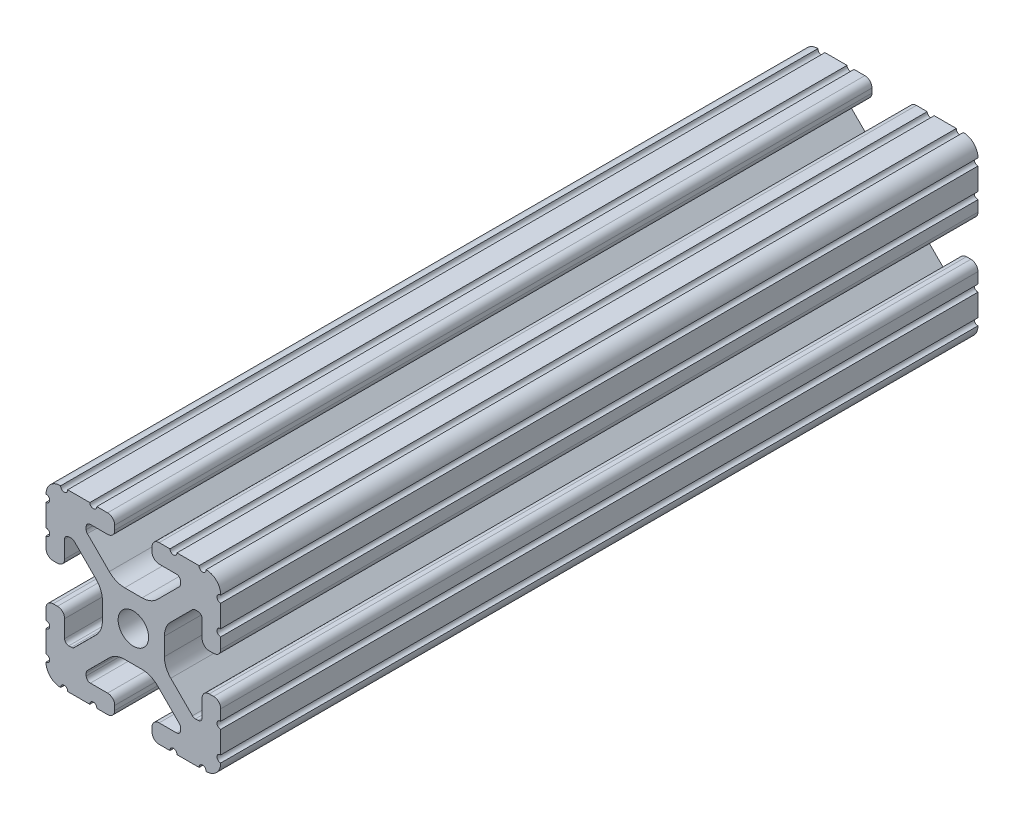
SolidWorks part; units mm, degrees
material "6061 Alloy"
ref_plane "Front Plane" through (0, 0, 0) normal (0, 0, 1) x (1, 0, 0)
ref_plane "Top Plane" through (0, 0, 0) normal (0, 1, 0) x (1, 0, 0)
ref_plane "Right Plane" through (0, 0, 0) normal (1, 0, 0) x (0, 0, -1)
sketch "Sketch1" plane through (0, 0, 0) normal (0, 0, 1) x (1, 0, 0)
  line L0 (0, 25.6181) -> (0, -24.623) construction
  line L1 (-20.8943, 0) -> (20.4607, 0) construction
  line L2 (-10.0229, 12.9148) -> (-5.2522, 8.144)
  line L3 (-10.287, 14.0843) -> (-10.287, 13.5524)
  line L4 (-5.6176, 14.986) -> (-9.3853, 14.986)
  line L5 (-4.064, 17.4964) -> (-4.064, 16.5396)
  line L6 (-7.9742, 19.05) -> (-5.6176, 19.05)
  line L7 (-14.3277, 19.05) -> (-9.4982, 19.05)
  line L8 (-19.05, 9.4961) -> (-19.05, 14.3277)
  line L9 (-19.05, 5.6176) -> (-19.05, 7.9763)
  line L10 (-16.5396, 4.064) -> (-17.4964, 4.064)
  line L11 (-14.986, 9.3853) -> (-14.986, 5.6176)
  line L12 (-13.516, 10.287) -> (-14.0843, 10.287)
  line L13 (-8.1476, 5.2921) -> (-12.8784, 10.0229)
  line L14 (-6.7564, -1.9335) -> (-6.7564, 1.9335)
  line L15 (-12.8784, -10.0229) -> (-8.1476, -5.2921)
  line L16 (-14.0843, -10.287) -> (-13.516, -10.287)
  line L17 (-14.986, -5.6176) -> (-14.986, -9.3853)
  line L18 (-17.4964, -4.064) -> (-16.5396, -4.064)
  line L19 (-19.05, -7.9763) -> (-19.05, -5.6176)
  line L20 (-19.05, -14.3277) -> (-19.05, -9.4961)
  line L21 (-9.4961, -19.05) -> (-14.3277, -19.05)
  line L22 (-5.6176, -19.05) -> (-7.9763, -19.05)
  line L23 (-4.064, -17.4964) -> (-4.064, -16.5396)
  line L24 (10.0229, -12.9148) -> (5.2522, -8.144)
  line L25 (10.287, -14.0843) -> (10.287, -13.5524)
  line L26 (5.6176, -14.986) -> (9.3853, -14.986)
  line L28 (-1.9022, 6.7564) -> (1.9022, 6.7564)
  line L29 (-1.9022, -6.7564) -> (1.9022, -6.7564)
  line L31 (-5.6176, -14.986) -> (-9.3853, -14.986)
  line L32 (-10.287, -14.0843) -> (-10.287, -13.5524)
  line L33 (-10.0229, -12.9148) -> (-5.2522, -8.144)
  line L66 (4.064, -16.5396) -> (4.064, -17.4964)
  line L67 (5.6176, -19.05) -> (7.9763, -19.05)
  line L68 (9.4961, -19.05) -> (14.3277, -19.05)
  line L69 (19.05, -14.3277) -> (19.05, -9.4961)
  line L70 (19.05, -7.9763) -> (19.05, -5.6176)
  line L71 (17.4964, -4.064) -> (16.5396, -4.064)
  line L72 (14.986, -5.6176) -> (14.986, -9.3853)
  line L73 (14.0843, -10.287) -> (13.516, -10.287)
  line L74 (12.8784, -10.0229) -> (8.1476, -5.2921)
  line L75 (6.7564, -1.9335) -> (6.7564, 1.9335)
  line L76 (8.1476, 5.2921) -> (12.8784, 10.0229)
  line L77 (13.516, 10.287) -> (14.0843, 10.287)
  line L78 (14.986, 9.3853) -> (14.986, 5.6176)
  line L79 (16.5396, 4.064) -> (17.4964, 4.064)
  line L80 (19.05, 5.6176) -> (19.05, 7.9763)
  line L81 (19.05, 9.4961) -> (19.05, 14.3277)
  line L82 (14.3277, 19.05) -> (9.4982, 19.05)
  line L83 (7.9742, 19.05) -> (5.6176, 19.05)
  line L84 (4.064, 17.4964) -> (4.064, 16.5396)
  line L85 (5.6176, 14.986) -> (9.3853, 14.986)
  line L86 (10.287, 14.0843) -> (10.287, 13.5524)
  line L87 (10.0229, 12.9148) -> (5.2522, 8.144)
  arc A0 (-10.0229, 12.9148) -> (-10.287, 13.5524) centre (-9.3853, 13.5524) cw
  circle A1 centre (0, 0) radius 3.3274
  arc A2 (-10.287, 14.0843) -> (-9.3853, 14.986) centre (-9.3853, 14.0843) cw
  arc A3 (-4.064, 16.5396) -> (-5.6176, 14.986) centre (-5.6176, 16.5396) cw
  arc A4 (-5.6176, 19.05) -> (-4.064, 17.4964) centre (-5.6176, 17.4964) cw
  arc A5 (-7.9742, 19.05) -> (-9.4982, 19.05) centre (-8.7362, 19.05) cw
  arc A6 (-14.3277, 19.05) -> (-15.8475, 19.05) centre (-15.0876, 18.9933) cw
  arc A7 (-19.05, 15.8475) -> (-15.8475, 19.05) centre (-15.8751, 15.8751) cw
  arc A8 (-19.05, 15.8475) -> (-19.05, 14.3277) centre (-18.9933, 15.0876) cw
  arc A9 (-19.05, 9.4961) -> (-19.05, 7.9763) centre (-18.9933, 8.7362) cw
  arc A10 (-17.4964, 4.064) -> (-19.05, 5.6176) centre (-17.4964, 5.6176) cw
  arc A11 (-14.986, 5.6176) -> (-16.5396, 4.064) centre (-16.5396, 5.6176) cw
  arc A12 (-14.986, 9.3853) -> (-14.0843, 10.287) centre (-14.0843, 9.3853) cw
  arc A13 (-13.516, 10.287) -> (-12.8784, 10.0229) centre (-13.516, 9.3853) cw
  arc A14 (-8.1476, 5.2921) -> (-6.7564, 1.9335) centre (-11.5062, 1.9335) cw
  arc A15 (-6.7564, -1.9335) -> (-8.1476, -5.2921) centre (-11.5062, -1.9335) cw
  arc A16 (-12.8784, -10.0229) -> (-13.516, -10.287) centre (-13.516, -9.3853) cw
  arc A17 (-14.0843, -10.287) -> (-14.986, -9.3853) centre (-14.0843, -9.3853) cw
  arc A18 (-16.5396, -4.064) -> (-14.986, -5.6176) centre (-16.5396, -5.6176) cw
  arc A19 (-19.05, -5.6176) -> (-17.4964, -4.064) centre (-17.4964, -5.6176) cw
  arc A20 (-19.05, -7.9763) -> (-19.05, -9.4961) centre (-18.9933, -8.7362) cw
  arc A21 (-19.05, -14.3277) -> (-19.05, -15.8475) centre (-18.9933, -15.0876) cw
  arc A22 (-15.8475, -19.05) -> (-19.05, -15.8475) centre (-15.8751, -15.8751) cw
  arc A23 (-15.8475, -19.05) -> (-14.3277, -19.05) centre (-15.0876, -18.9933) cw
  arc A24 (-9.4961, -19.05) -> (-7.9763, -19.05) centre (-8.7362, -18.9933) cw
  arc A25 (-4.064, -17.4964) -> (-5.6176, -19.05) centre (-5.6176, -17.4964) cw
  arc A26 (-5.2522, -8.144) -> (-1.9022, -6.7564) centre (-1.9022, -11.494) cw
  arc A27 (1.9022, -6.7564) -> (5.2522, -8.144) centre (1.9022, -11.494) cw
  arc A28 (10.0229, -12.9148) -> (10.287, -13.5524) centre (9.3853, -13.5524) cw
  arc A29 (10.287, -14.0843) -> (9.3853, -14.986) centre (9.3853, -14.0843) cw
  arc A30 (4.064, -16.5396) -> (5.6176, -14.986) centre (5.6176, -16.5396) cw
  arc A31 (-4.064, -16.5396) -> (-5.6176, -14.986) centre (-5.6176, -16.5396) ccw
  arc A32 (-10.287, -14.0843) -> (-9.3853, -14.986) centre (-9.3853, -14.0843) ccw
  arc A33 (-10.0229, -12.9148) -> (-10.287, -13.5524) centre (-9.3853, -13.5524) ccw
  arc A79 (4.064, -17.4964) -> (5.6176, -19.05) centre (5.6176, -17.4964) ccw
  arc A80 (9.4961, -19.05) -> (7.9763, -19.05) centre (8.7362, -18.9933) ccw
  arc A81 (15.8475, -19.05) -> (14.3277, -19.05) centre (15.0876, -18.9933) ccw
  arc A82 (15.8475, -19.05) -> (19.05, -15.8475) centre (15.8751, -15.8751) ccw
  arc A83 (19.05, -14.3277) -> (19.05, -15.8475) centre (18.9933, -15.0876) ccw
  arc A84 (19.05, -7.9763) -> (19.05, -9.4961) centre (18.9933, -8.7362) ccw
  arc A85 (19.05, -5.6176) -> (17.4964, -4.064) centre (17.4964, -5.6176) ccw
  arc A86 (16.5396, -4.064) -> (14.986, -5.6176) centre (16.5396, -5.6176) ccw
  arc A87 (14.0843, -10.287) -> (14.986, -9.3853) centre (14.0843, -9.3853) ccw
  arc A88 (12.8784, -10.0229) -> (13.516, -10.287) centre (13.516, -9.3853) ccw
  arc A89 (6.7564, -1.9335) -> (8.1476, -5.2921) centre (11.5062, -1.9335) ccw
  arc A90 (8.1476, 5.2921) -> (6.7564, 1.9335) centre (11.5062, 1.9335) ccw
  arc A91 (13.516, 10.287) -> (12.8784, 10.0229) centre (13.516, 9.3853) ccw
  arc A92 (14.986, 9.3853) -> (14.0843, 10.287) centre (14.0843, 9.3853) ccw
  arc A93 (14.986, 5.6176) -> (16.5396, 4.064) centre (16.5396, 5.6176) ccw
  arc A94 (17.4964, 4.064) -> (19.05, 5.6176) centre (17.4964, 5.6176) ccw
  arc A95 (19.05, 9.4961) -> (19.05, 7.9763) centre (18.9933, 8.7362) ccw
  arc A96 (19.05, 15.8475) -> (19.05, 14.3277) centre (18.9933, 15.0876) ccw
  arc A97 (19.05, 15.8475) -> (15.8475, 19.05) centre (15.8751, 15.8751) ccw
  arc A98 (14.3277, 19.05) -> (15.8475, 19.05) centre (15.0876, 18.9933) ccw
  arc A99 (7.9742, 19.05) -> (9.4982, 19.05) centre (8.7362, 19.05) ccw
  arc A100 (5.6176, 19.05) -> (4.064, 17.4964) centre (5.6176, 17.4964) ccw
  arc A101 (4.064, 16.5396) -> (5.6176, 14.986) centre (5.6176, 16.5396) ccw
  arc A102 (10.287, 14.0843) -> (9.3853, 14.986) centre (9.3853, 14.0843) ccw
  arc A103 (10.0229, 12.9148) -> (10.287, 13.5524) centre (9.3853, 13.5524) ccw
  arc A104 (1.9022, 6.7564) -> (5.2522, 8.144) centre (1.9022, 11.494) ccw
  arc A105 (-5.2522, 8.144) -> (-1.9022, 6.7564) centre (-1.9022, 11.494) ccw
  dimension "D1" = 6.6548
  dimension "D2" = 19.05
  dimension "D3" = 38.1
  dimension "D4" = 20.574
  dimension "D5" = 13.5128
  dimension "D6" = 4.064
  dimension "D7" = 8.128
  dimension "D8" = 4.064
  dimension "D9" = 12.2936
extrude "Extrude1" add sketch "Sketch1" against normal blind 165.1
